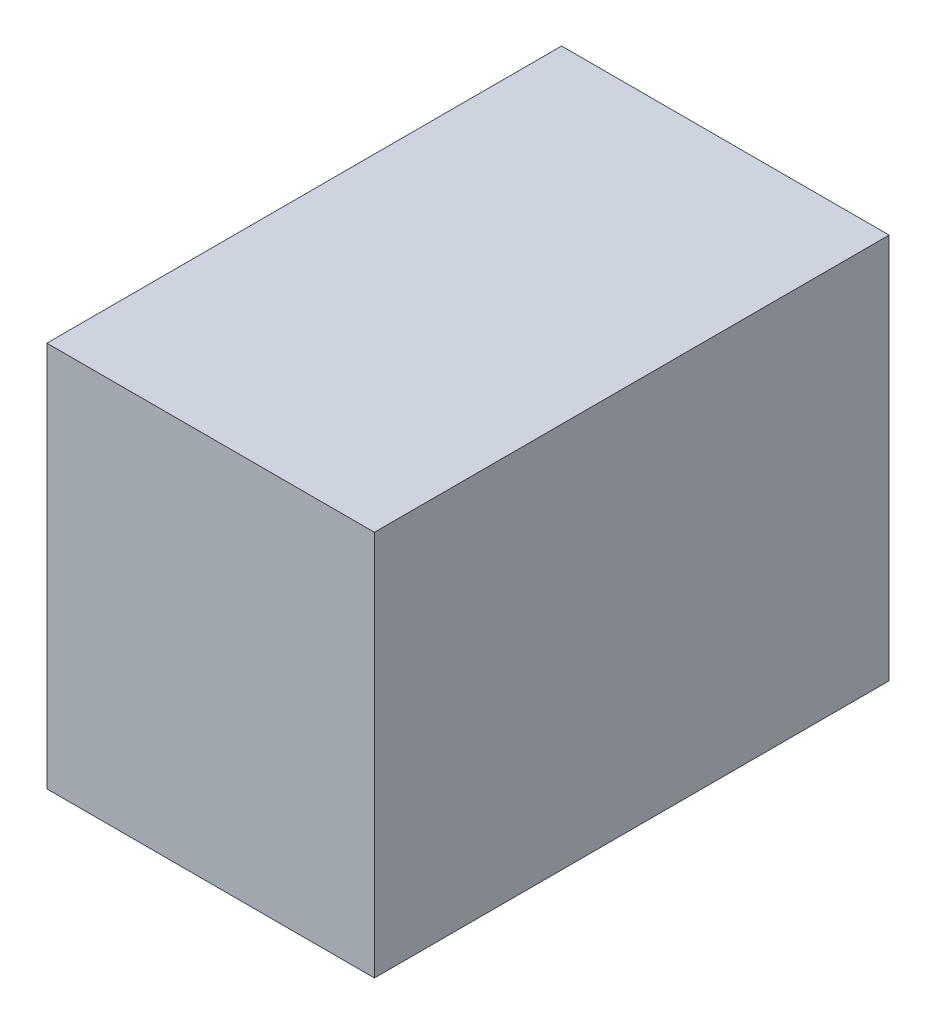
SolidWorks part; units mm, degrees
ref_plane "Front Plane" through (0, 0, 0) normal (0, 0, 1) x (1, 0, 0)
ref_plane "Top Plane" through (0, 0, 0) normal (0, 1, 0) x (1, 0, 0)
ref_plane "Right Plane" through (0, 0, 0) normal (1, 0, 0) x (0, 0, -1)
sketch "Sketch1" plane through (0, 0, 0) normal (0, 1, 0) x (1, 0, 0)
  line L1 (70, -110) -> (-70, -110)
  line L2 (70, -110) -> (70, 110)
  line L3 (70, 110) -> (-70, 110)
  line L4 (-70, -110) -> (-70, 110)
  line L5 (70, -110) -> (-70, 110) construction
  line L6 (70, 110) -> (-70, -110) construction
  point P0 (0, 0)
  dimension "D1" = 220
  dimension "D2" = 140
extrude "Boss-Extrude1" add sketch "Sketch1" along normal blind 165
shell "Shell1" thickness 2
